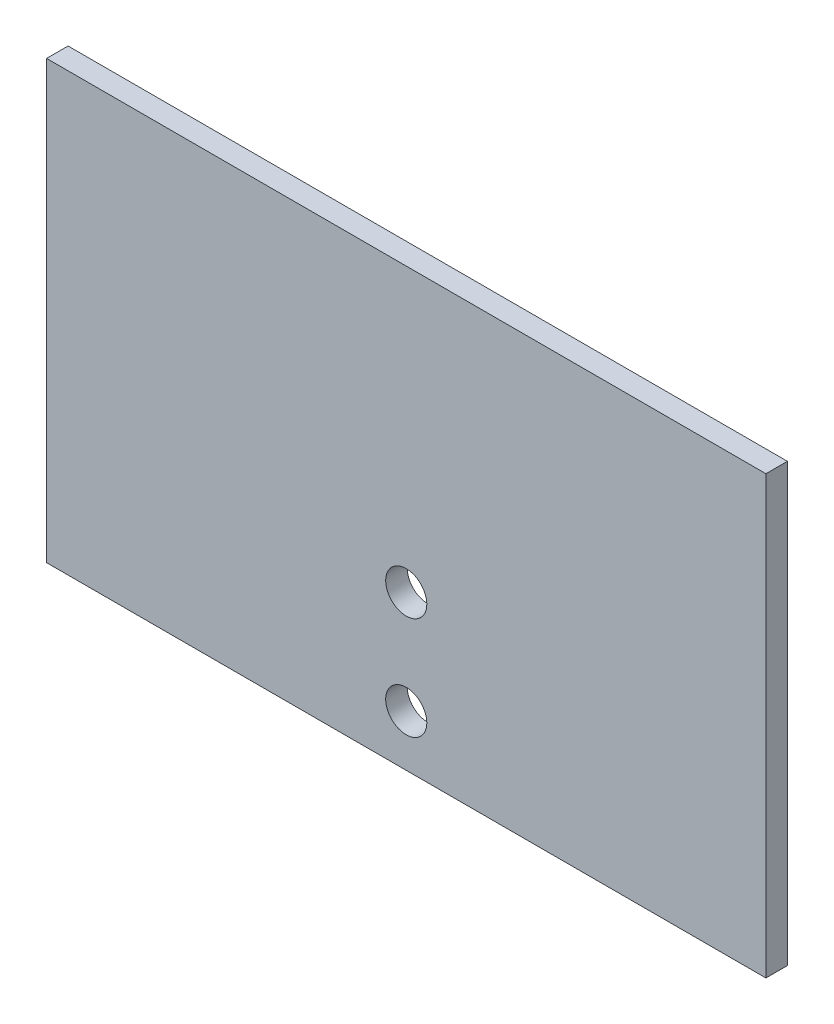
SolidWorks part; units mm, degrees
material "1060 Alloy"
ref_plane "Front Plane" through (0, 0, 0) normal (0, 0, 1) x (1, 0, 0)
ref_plane "Top Plane" through (0, 0, 0) normal (0, 1, 0) x (1, 0, 0)
ref_plane "Right Plane" through (0, 0, 0) normal (1, 0, 0) x (0, 0, -1)
sketch "Sketch1" plane through (0, 0, 0) normal (0, 0, 1) x (1, 0, 0)
  line L1 (0, 0) -> (88.9, 0)
  line L2 (0, 0) -> (0, 53.975)
  line L3 (0, 53.975) -> (88.9, 53.975)
  line L4 (88.9, 0) -> (88.9, 53.975)
  dimension "D1" = 88.9
  dimension "D2" = 53.975
extrude "Boss-Extrude1" add sketch "Sketch1" along normal blind 2.6568
sketch "Sketch2" plane through (0, 0, 2.6568) normal (0, 0, 1) x (1, 0, 0)
  line L0 (44.45, 0) -> (44.45, 6.35) construction
  line L1 (0, 0) -> (88.9, 0) construction
  line L2 (44.45, 6.35) -> (44.45, 19.05) construction
  line L3 (44.45, 19.05) -> (44.45, 31.75) construction
  line L4 (88.9, 53.975) -> (0, 53.975) construction
  circle A0 centre (44.45, 6.35) radius 2.54
  circle A1 centre (44.45, 19.05) radius 2.54
  dimension "D1" = 5.08
  dimension "D2" = 12.7
  dimension "D3" = 6.35
  dimension "D4" = 22.225
extrude "Cut-Extrude1" cut sketch "Sketch2" against normal through all
